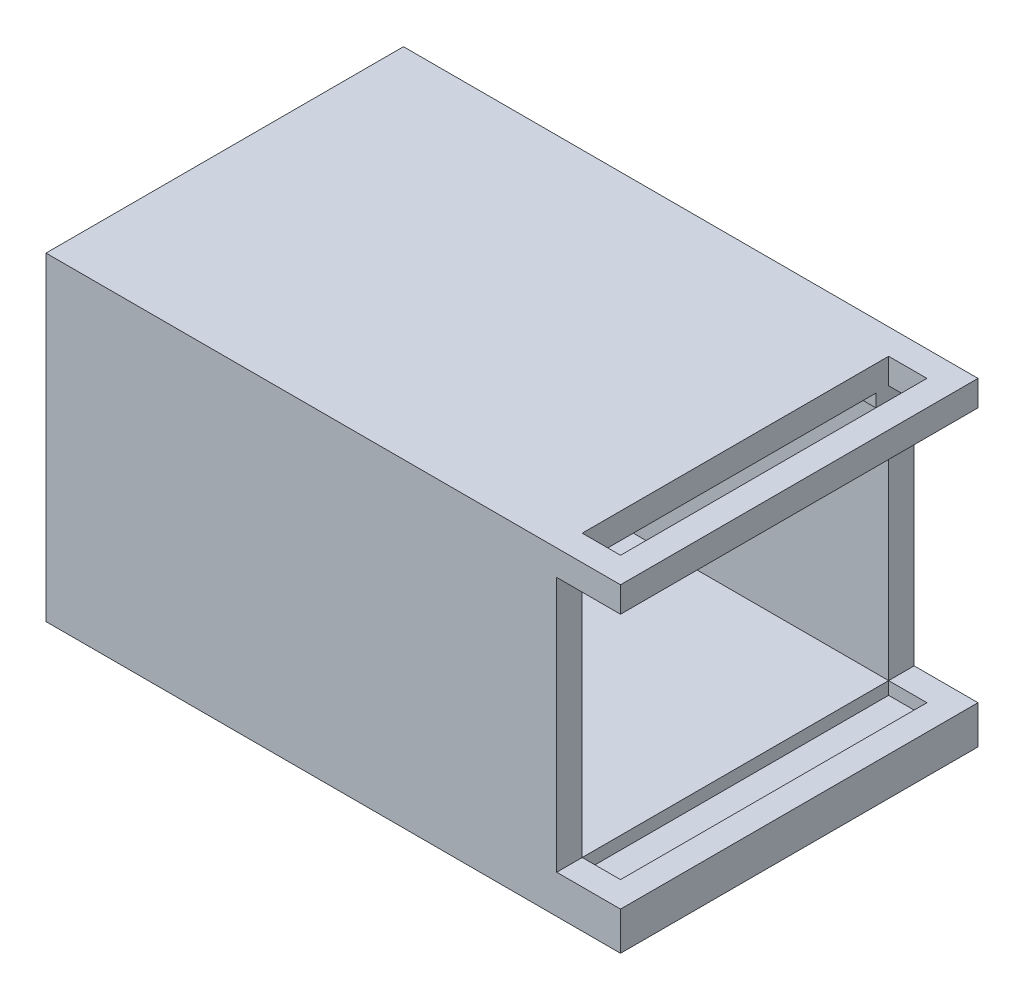
SolidWorks part; units mm, degrees
ref_plane "Front Plane" through (0, 0, 0) normal (0, 0, 1) x (1, 0, 0)
ref_plane "Top Plane" through (0, 0, 0) normal (0, 1, 0) x (1, 0, 0)
ref_plane "Right Plane" through (0, 0, 0) normal (1, 0, 0) x (0, 0, -1)
sketch "Sketch1" plane through (0, 0, 0) normal (0, 1, 0) x (1, 0, 0)
  line L1 (0, 0) -> (45, 0)
  line L2 (0, 0) -> (0, 28)
  line L3 (0, 28) -> (45, 28)
  line L4 (45, 0) -> (45, 28)
  dimension "D1" = 28
  dimension "D2" = 45
extrude "Boss-Extrude1" add sketch "Sketch1" along normal blind 3 contours L2 L1 L4 L3
sketch "Sketch2" plane through (0, 3, 0) normal (0, 1, 0) x (1, 0, 0)
  line L0 (40, 26) -> (40, 28)
  line L1 (0, 28) -> (40, 28)
  line L2 (0, 28) -> (0, 0)
  line L3 (0, 0) -> (40, 0)
  line L5 (2, 26) -> (40, 26)
  line L6 (2, 26) -> (2, 2)
  line L7 (2, 2) -> (40, 2)
  line L9 (40, 2) -> (40, 0)
  line L10 (45, 0) -> (45, 28) construction
  line L11 (0, 0) -> (45, 0) construction
  dimension "D1" = 2
  dimension "D2" = 2
  dimension "D3" = 2
  dimension "D4" = 5
  dimension "D5" = 5
extrude "Boss-Extrude2" add sketch "Sketch2" along normal blind 22 contours L5 L0 L1 L2 L3 L9 L7 L6
sketch "Sketch4" plane through (0, 25, 0) normal (0, 1, 0) x (1, 0, 0)
  line L0 (0, 28) -> (40, 28) construction
  line L1 (0, 28) -> (45, 28)
  line L2 (0, 28) -> (0, 0)
  line L3 (0, 0) -> (45, 0)
  line L4 (45, 28) -> (45, 0)
  line L5 (2, 2) -> (40, 2) construction
  line L6 (40, 26) -> (43, 26)
  line L7 (40, 26) -> (40, 2)
  line L8 (40, 2) -> (43, 2)
  line L9 (43, 26) -> (43, 2)
  dimension "D1" = 2
extrude "Boss-Extrude4" add sketch "Sketch4" against normal blind 2
sketch "Sketch5" plane through (0, 0, 0) normal (-1, 0, 0) x (0, 0, 1)
  line L0 (-18.47, 5.25) -> (-18.47, 5.96)
  line L1 (-17.22, 4) -> (-10.78, 4)
  line L2 (-17.22, 7.21) -> (-10.78, 7.21)
  line L3 (-9.53, 5.96) -> (-9.53, 5.25)
  line L4 (0, 0) -> (-28, 0) construction
  line L5 (-28, 25) -> (-28, 0) construction
  line L7 (-18.25, 12) -> (-9.75, 12)
  line L8 (-18.25, 12) -> (-18.25, 8.5)
  line L9 (-18.25, 8.5) -> (-9.75, 8.5)
  line L10 (-9.75, 12) -> (-9.75, 8.5)
  arc A0 (-18.47, 5.25) -> (-17.22, 4) centre (-17.22, 5.25) ccw
  arc A1 (-17.22, 7.21) -> (-18.47, 5.96) centre (-17.22, 5.96) ccw
  arc A2 (-9.53, 5.96) -> (-10.78, 7.21) centre (-10.78, 5.96) ccw
  arc A3 (-10.78, 4) -> (-9.53, 5.25) centre (-10.78, 5.25) ccw
  dimension "D7" = 1.25
  dimension "D1" = 1.25
  dimension "D2" = 0.71
  dimension "D3" = 6.44
  dimension "D4" = 1.25
  dimension "D5" = 1.25
  dimension "D6" = 6.44
  dimension "D8" = 3.21
  dimension "D9" = 0.71
  dimension "D10" = 4
  dimension "D11" = 9.53
  dimension "D12" = 3.5
  dimension "D13" = 8.5
  dimension "D14" = 1.29
  dimension "D15" = 0.22
extrude "Cut-Extrude1" cut sketch "Sketch5" against normal blind 2
sketch "Sketch7" plane through (0, 23, 0) normal (0, -1, 0) x (1, 0, 0)
  line L0 (40, -26) -> (40, -2) construction
  line L1 (40, -25) -> (5, -25)
  line L3 (40, -3) -> (5, -3)
  line L4 (5, -25) -> (5, -3)
  line L5 (2, -26) -> (2, -2) construction
  line L6 (2, -26) -> (40, -26) construction
  line L7 (2, -2) -> (40, -2) construction
  line L8 (40, -25) -> (40, -26)
  line L9 (2, -2) -> (40, -2)
  line L10 (2, -2) -> (2, -26)
  line L11 (2, -26) -> (40, -26)
  line L12 (40, -2) -> (40, -3)
  dimension "D1" = 3
  dimension "D2" = 1
  dimension "D3" = 1
extrude "Boss-Extrude6" add sketch "Sketch7" along normal blind 1
sketch "Sketch8" plane through (0, 3, 0) normal (0, 1, 0) x (1, 0, 0)
  line L1 (40, 2) -> (43, 2)
  line L2 (40, 2) -> (40, 26)
  line L3 (40, 26) -> (43, 26)
  line L4 (43, 2) -> (43, 26)
  line L5 (2, 26) -> (40, 26) construction
  dimension "D1" = 3
extrude "Cut-Extrude2" cut sketch "Sketch8" against normal blind 1 contours L2 L1 L4 L3
